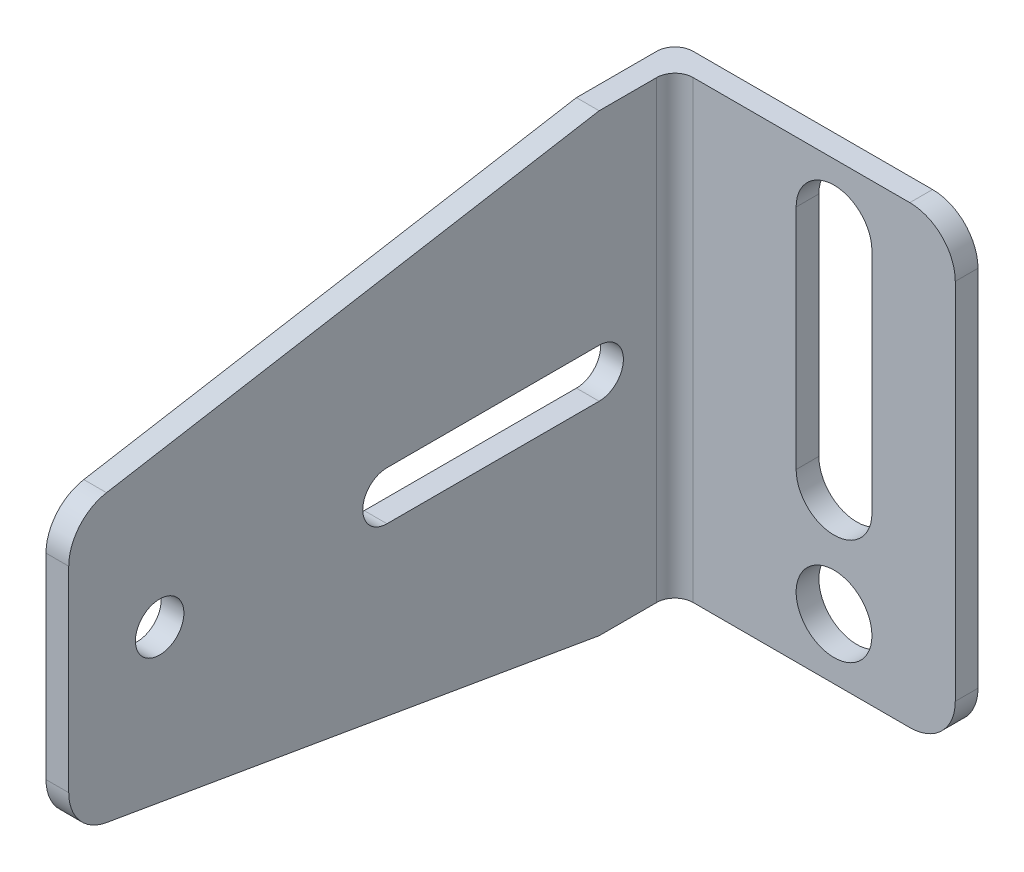
SolidWorks part; units mm, degrees
material "Alloy Steel"
ref_plane "Front Plane" through (0, 0, 0) normal (0, 0, 1) x (1, 0, 0)
ref_plane "Top Plane" through (0, 0, 0) normal (0, 1, 0) x (1, 0, 0)
ref_plane "Right Plane" through (0, 0, 0) normal (1, 0, 0) x (0, 0, -1)
sketch "Sketch1" plane through (0, 0, 0) normal (0, 0, 1) x (1, 0, 0)
  line L1 (0, 0) -> (20, 0)
  line L2 (0, 0) -> (0, -30)
  line L3 (0, -30) -> (20, -30)
  line L4 (20, 0) -> (20, -30)
  line L5 (12, -4) -> (12, -19) construction
  line L6 (14.5, -4) -> (14.5, -19)
  line L7 (9.5, -4) -> (9.5, -19)
  arc A0 (14.5, -4) -> (9.5, -4) centre (12, -4) ccw
  arc A1 (9.5, -19) -> (14.5, -19) centre (12, -19) ccw
  circle A2 centre (12, -26) radius 2.5
  point P9 (12, -11.5)
  dimension "D6" = 5
  dimension "D1" = 30
  dimension "D2" = 20
  dimension "D3" = 5
  dimension "D4" = 15
  dimension "D5" = 4
  dimension "D7" = 4
  dimension "D8" = 12
  dimension "D9" = 12
extrude "Boss-Extrude1" add sketch "Sketch1" along normal blind 1.5
sketch "Sketch3" plane through (0, 0, 0) normal (-1, 0, 0) x (0, 0, 1)
  line L0 (1.5, 0) -> (1.5, -30)
  line L1 (1.5, -30) -> (6.5, -30)
  line L2 (6.5, -30) -> (41.5, -24)
  line L3 (41.5, -24) -> (41.5, -6)
  line L4 (41.5, -6) -> (6.5, 0)
  line L5 (6.5, 0) -> (1.5, 0)
  line L6 (1.5, -15) -> (47.4967, -15) construction
  line L7 (6.5, -15) -> (20.5, -15) construction
  line L8 (6.5, -13.4) -> (20.5, -13.4)
  line L9 (6.5, -16.6) -> (20.5, -16.6)
  circle A0 centre (35.5, -15) radius 1.6
  arc A1 (6.5, -13.4) -> (6.5, -16.6) centre (6.5, -15) ccw
  arc A2 (20.5, -16.6) -> (20.5, -13.4) centre (20.5, -15) ccw
  point P14 (13.5, -15)
  dimension "D6" = 3.2
  dimension "D1" = 40
  dimension "D2" = 5
  dimension "D3" = 5
  dimension "D4" = 18
  dimension "D5" = 9
  dimension "D7" = 6
  dimension "D8" = 14
  dimension "D9" = 3.2
  dimension "D10" = 15
extrude "Boss-Extrude2" add sketch "Sketch3" against normal blind 1.5
fillet "Fillet1" radius 1.2 2 edges at (0, -15, 0) (1.5, -15, 1.5)
fillet "Fillet2" radius 3 4 edges at (0.75, -24, 41.5) (0.75, -6, 41.5) (20, -30, 0.75) (20, 0, 0.75)
